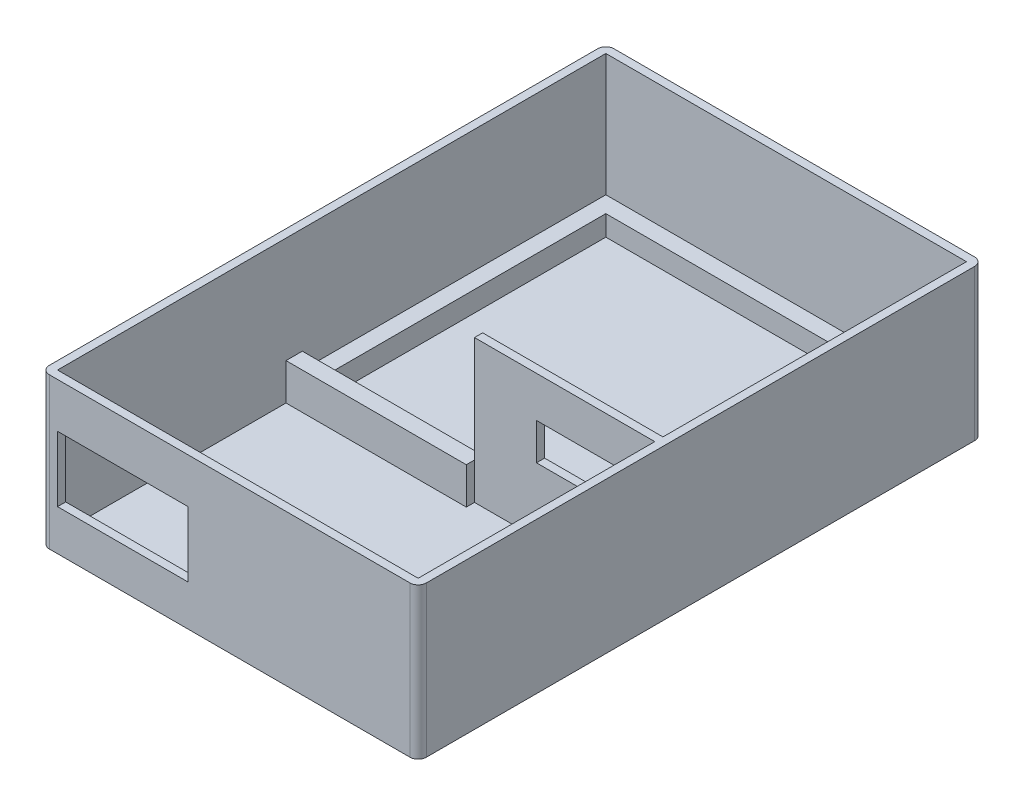
SolidWorks part; units mm, degrees
ref_plane "Front Plane" through (0, 0, 0) normal (0, 0, 1) x (1, 0, 0)
ref_plane "Top Plane" through (0, 0, 0) normal (0, 1, 0) x (1, 0, 0)
ref_plane "Right Plane" through (0, 0, 0) normal (1, 0, 0) x (0, 0, -1)
sketch "Sketch1" plane through (0, 0, 0) normal (0, 1, 0) x (1, 0, 0)
  line L0 (-23.1, -19.6) -> (-23.1, 19.6)
  line L1 (-20.1, -16.6) -> (20.1, -16.6)
  line L2 (-20.1, -16.6) -> (-20.1, 16.6)
  line L3 (-20.1, 16.6) -> (20.1, 16.6)
  line L4 (20.1, -16.6) -> (20.1, 16.6)
  line L5 (-20.1, -16.6) -> (20.1, 16.6) construction
  line L6 (-20.1, 16.6) -> (20.1, -16.6) construction
  line L7 (-23.1, 19.6) -> (23.1, 19.6)
  line L8 (23.1, -19.6) -> (23.1, 19.6)
  line L9 (-23.1, -19.6) -> (23.1, -19.6)
  point P0 (0, 0)
  dimension "D1" = 40.2
  dimension "D2" = 33.2
  dimension "D3" = 3
extrude "Boss-Extrude1" add sketch "Sketch1" along normal blind 2.5
sketch "Sketch3" plane through (0, 0, 0) normal (0, -1, 0) x (1, 0, 0)
  line L1 (23.1, -19.6) -> (-23.1, -19.6)
  line L2 (23.1, -19.6) -> (23.1, 19.6)
  line L3 (23.1, 19.6) -> (-23.1, 19.6)
  line L4 (-23.1, -19.6) -> (-23.1, 19.6)
  line L5 (23.1, -19.6) -> (-23.1, 19.6) construction
  line L6 (23.1, 19.6) -> (-23.1, -19.6) construction
  point P0 (0, 0)
extrude "Boss-Extrude2" add sketch "Sketch3" along normal blind 1
sketch "Sketch4" plane through (0, 2.5, 0) normal (0, 1, 0) x (1, 0, 0)
  line L0 (23.1, 19.6) -> (-23.1, 19.6) construction
  line L1 (23.1, -19.6) -> (-23.1, -19.6)
  line L2 (23.1, -19.6) -> (23.1, 19.6)
  line L3 (23.1, 19.6) -> (-23.1, 19.6)
  line L4 (-23.1, -19.6) -> (-23.1, 19.6)
  line L5 (23.1, -19.6) -> (-23.1, 19.6) construction
  line L6 (23.1, 19.6) -> (-23.1, -19.6) construction
  line L7 (-23.1, 19.6) -> (-23.1, -19.6) construction
  line L8 (-22.1, -18.6) -> (-22.1, 18.6)
  line L9 (22.1, 18.6) -> (-22.1, 18.6)
  line L10 (22.1, -18.6) -> (22.1, 18.6)
  line L11 (22.1, -18.6) -> (-22.1, -18.6)
  point P0 (0, 0)
  dimension "D1" = 1
extrude "Boss-Extrude3" add sketch "Sketch4" along normal blind 15
sketch "Sketch5" plane through (0, 0, 18.6) normal (0, 0, -1) x (-1, 0, 0)
  line L0 (-22.1, 17.5) -> (-22.1, 2.5) construction
  line L1 (-7.6, 8) -> (-17.1, 8)
  line L2 (-7.6, 8) -> (-7.6, 12.5)
  line L3 (-7.6, 12.5) -> (-17.1, 12.5)
  line L4 (-17.1, 8) -> (-17.1, 12.5)
  line L5 (-7.6, 8) -> (-17.1, 12.5) construction
  line L6 (-7.6, 12.5) -> (-17.1, 8) construction
  line L7 (22.1, 2.5) -> (-22.1, 2.5) construction
  point P0 (-12.35, 10.25)
  dimension "D1" = 4.5
  dimension "D2" = 9.5
  dimension "D3" = 5
  dimension "D4" = 5.5
extrude "Cut-Extrude1" cut sketch "Sketch5" against normal blind 15
sketch "Sketch6" plane through (0, -1, 0) normal (0, -1, 0) x (1, 0, 0)
  line L1 (-23.1, 19.6) -> (23.1, 19.6)
  line L2 (-23.1, 19.6) -> (-23.1, 49.6)
  line L3 (-23.1, 49.6) -> (23.1, 49.6)
  line L4 (23.1, 19.6) -> (23.1, 49.6)
  dimension "D1" = 30
extrude "Boss-Extrude4" add sketch "Sketch6" against normal blind 1
sketch "Sketch7" plane through (0, 0, 0) normal (0, 1, 0) x (1, 0, 0)
  line L0 (-22.1, -20.6) -> (-22.1, -48.6)
  line L1 (-22.1, -48.6) -> (22.1, -48.6)
  line L2 (22.1, -48.6) -> (22.1, -20.6)
  line L3 (22.1, -20.6) -> (-22.1, -20.6)
  line L4 (-23.1, -19.6) -> (-23.1, -49.6)
  line L5 (-23.1, -49.6) -> (23.1, -49.6)
  line L6 (23.1, -49.6) -> (23.1, -19.6)
  line L7 (23.1, -19.6) -> (-23.1, -19.6)
  line L8 (-23.1, -19.6) -> (-23.1, -49.6)
  line L9 (-23.1, -49.6) -> (23.1, -49.6)
  line L10 (23.1, -49.6) -> (23.1, -19.6)
  line L11 (23.1, -19.6) -> (-23.1, -19.6)
  dimension "D1" = 0
  dimension "D2" = 1
extrude "Boss-Extrude5" add sketch "Sketch7" along normal up to surface (17.5 mm away) up to face at (0, 17.5, 0)
sketch "Sketch8" plane through (0, 17.5, 0) normal (0, 1, 0) x (1, 0, 0)
  line L0 (22.1, -20.6) -> (-22.1, -20.6) construction
  line L1 (-22.1, -18.6) -> (0, -18.6)
  line L2 (-22.1, -18.6) -> (-22.1, -20.6)
  line L3 (-22.1, -20.6) -> (0, -20.6)
  line L4 (0, -18.6) -> (0, -20.6)
extrude "Cut-Extrude2" cut sketch "Sketch8" against normal offset from surface (13 mm away) 2 up to face at (0, 2.5, 0)
sketch "Sketch9" plane through (0, 17.5, 0) normal (0, 1, 0) x (1, 0, 0)
  line L0 (0, -20.6) -> (0, -18.6) construction
  line L1 (0, -19.6) -> (22.1, -19.6)
  line L2 (0, -19.6) -> (0, -20.6)
  line L3 (0, -20.6) -> (22.1, -20.6)
  line L4 (22.1, -19.6) -> (22.1, -20.6)
extrude "Cut-Extrude3" cut sketch "Sketch9" against normal up to surface (17.5 mm away) up to face at (0, 0, 34.6)
sketch "Sketch10" plane through (0, 0, 49.6) normal (0, 0, 1) x (1, 0, 0)
  line L0 (-23.1, 17.5) -> (-23.1, -1) construction
  line L1 (-21.1, 4) -> (-5.1, 4)
  line L2 (-21.1, 4) -> (-21.1, 12)
  line L3 (-21.1, 12) -> (-5.1, 12)
  line L4 (-5.1, 4) -> (-5.1, 12)
  line L5 (23.1, -1) -> (-23.1, -1) construction
  dimension "D1" = 8
  dimension "D2" = 16
  dimension "D3" = 2
  dimension "D4" = 5
extrude "Cut-Extrude4" cut sketch "Sketch10" against normal blind 10
fillet "Fillet1" radius 1 4 edges at (-23.1, 8.25, -19.6) (23.1, 8.25, -19.6) (23.1, 8.25, 49.6) (-23.1, 8.25, 49.6)
